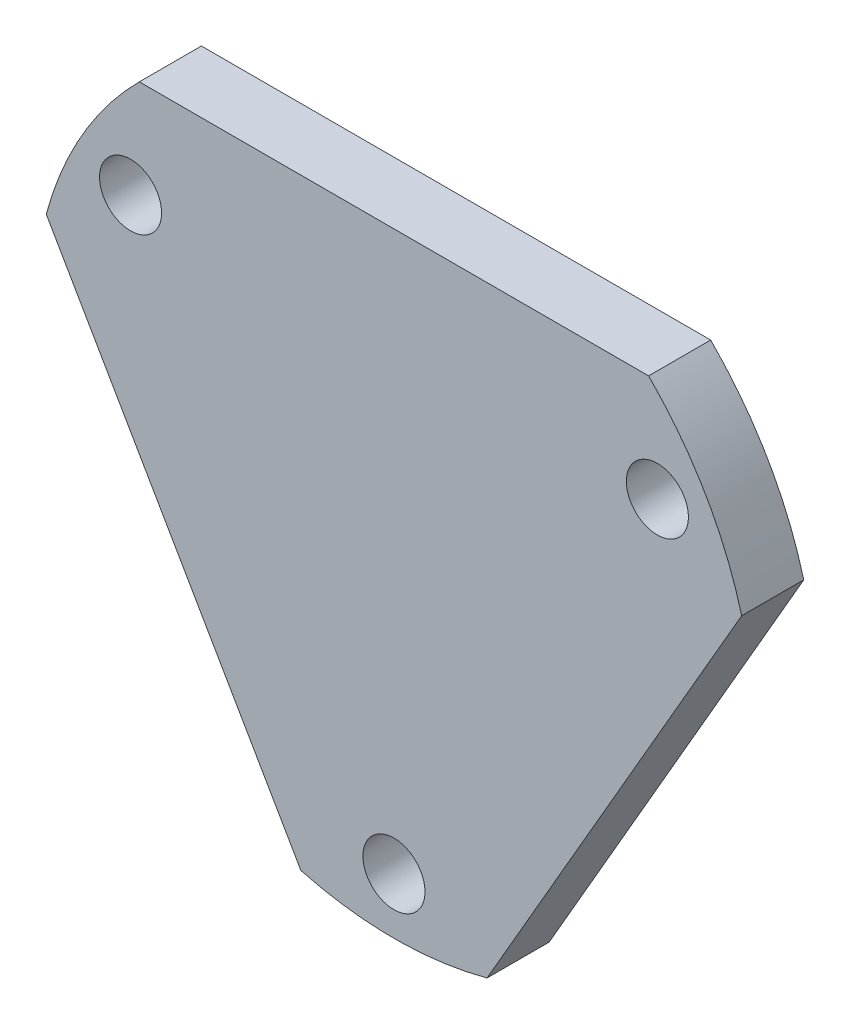
SolidWorks part; units mm, degrees
ref_plane "Front" through (0, 0, 0) normal (0, 0, 1) x (1, 0, 0)
ref_plane "Top" through (0, 0, 0) normal (0, 1, 0) x (1, 0, 0)
ref_plane "Right" through (0, 0, 0) normal (1, 0, 0) x (0, 0, -1)
sketch "Эскиз1" plane through (0, 0, 0) normal (0, 0, -1) x (1, 0, 0)
  line L0 (-10.2561, -10.25) -> (10.2561, -10.25)
  line L1 (0, 20.5) -> (-17.7535, -10.25) construction
  line L2 (-17.7535, -10.25) -> (17.7535, -10.25) construction
  line L3 (17.7535, -10.25) -> (0, 20.5) construction
  line L4 (-14.0048, -3.757) -> (-3.7487, 14.007)
  line L5 (3.7487, 14.007) -> (14.0048, -3.757)
  line L6 (7.0475, 14.5) -> (-2.501, 14.5) construction
  line L7 (7.0475, 13.5) -> (-2.501, 13.5) construction
  line L8 (0, 12.25) -> (0, 0) construction
  circle A0 centre (0, 0) radius 10.25 construction
  circle A1 centre (0, 0) radius 14.5 construction
  circle A3 centre (0, 12.25) radius 1.25
  circle A5 centre (0, 0) radius 12.25 construction
  circle A6 centre (10.6088, -6.125) radius 1.25
  circle A7 centre (-10.6088, -6.125) radius 1.25
  arc A8 (-3.7487, 14.007) -> (3.7487, 14.007) centre (0, 0) cw
  arc A9 (14.0048, -3.757) -> (10.2561, -10.25) centre (0, 0) cw
  arc A10 (-10.2561, -10.25) -> (-14.0048, -3.757) centre (0, 0) cw
  point P7 (0, 0)
  point P10 (0, 0)
  point P11 (0, 0)
  point P12 (0, 0)
  point P13 (0, 0)
  point P27 (0, 0)
  point P28 (0, 0)
  point P31 (0, 0)
  point P32 (0, 0)
  dimension "D1" = 20.5
  dimension "D2" = 29
  dimension "D4" = 1
  dimension "D5" = 2.5
  dimension "D6" = 3
  dimension "D7" = 22.5
  dimension "D3" = 20.5122
extrude "Бобышка-Вытянуть1" add sketch "Эскиз1" along normal blind 2.5
